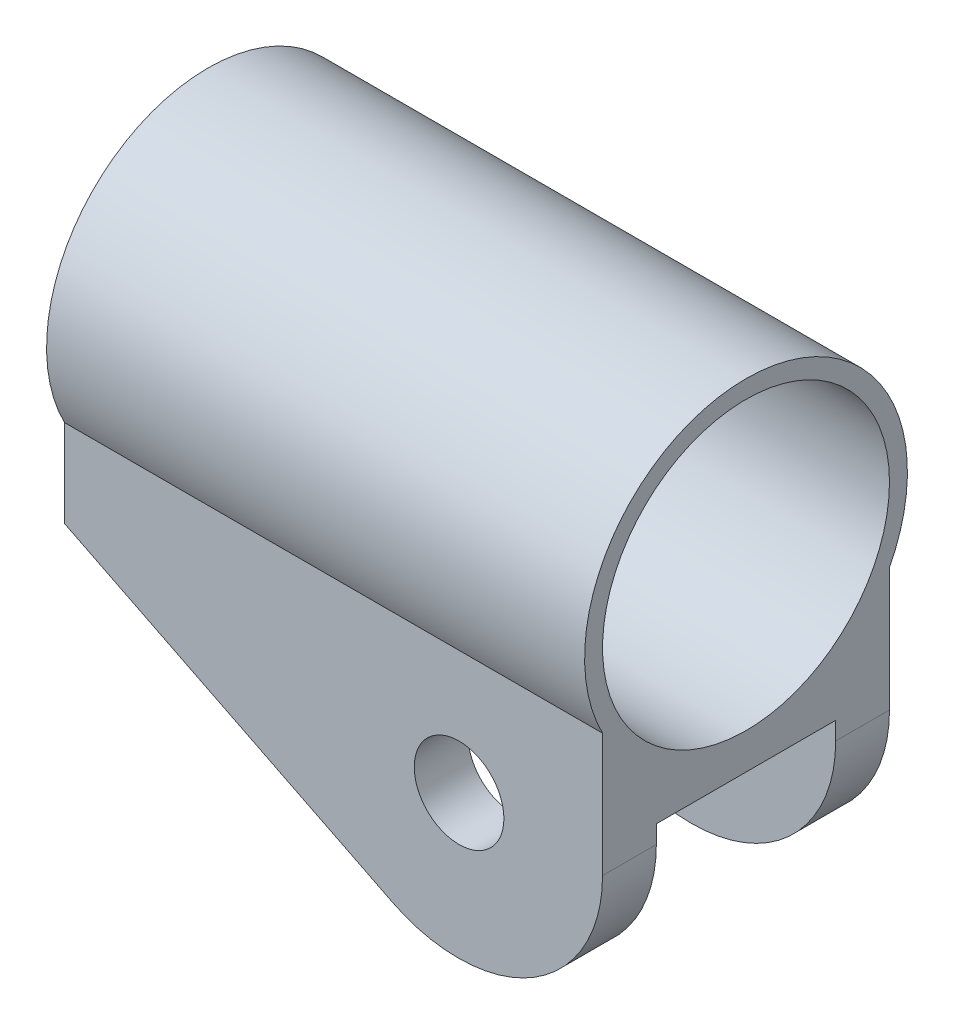
SolidWorks part; units mm, degrees
material "ABS"
ref_plane "Front Plane" through (0, 0, 0) normal (0, 0, 1) x (1, 0, 0)
ref_plane "Top Plane" through (0, 0, 0) normal (0, 1, 0) x (1, 0, 0)
ref_plane "Right Plane" through (0, 0, 0) normal (1, 0, 0) x (0, 0, -1)
sketch "Sketch1" plane through (0, 0, 0) normal (1, 0, 0) x (0, 0, -1)
  circle A0 centre (0, 0) radius 8
  circle A1 centre (0, 0) radius 9
  dimension "D1" = 16
  dimension "D2" = 1
extrude "Boss-Extrude1" add sketch "Sketch1" along normal blind 30
ref_plane "Plane1" through (0, -9, 0) normal (0, -1, 0) x (-1, 0, 0)
sketch "Sketch2" plane through (0, -9, 0) normal (0, -1, 0) x (-1, 0, 0)
  line L0 (0, -9) -> (0, 9) construction
  line L1 (-30, 9) -> (-30, -9) construction
  line L2 (0, -8) -> (-30, -8)
  line L3 (0, -8) -> (0, 8)
  line L4 (0, 8) -> (-30, 8)
  line L5 (-30, -8) -> (-30, 8)
  dimension "D1" = 8
  dimension "D2" = 8
extrude "Boss-Extrude2" add sketch "Sketch2" along normal blind 10 and the other way up to surface
sketch "Sketch3" plane through (0, 0, 8) normal (0, 0, 1) x (1, 0, 0)
  line L0 (0, -19) -> (0, -9)
  line L1 (-9.9, -9) -> (9.9, -9) construction
  line L2 (0, -19) -> (0, -4.1231) construction
  line L3 (0, -9) -> (20, -19)
  line L4 (30, -19) -> (0, -19) construction
  line L5 (20, -19) -> (0, -19)
  line L6 (30, -19) -> (30, -4.1231) construction
  dimension "D1" = 10
extrude "Cut-Extrude1" cut sketch "Sketch3" against normal through all
sketch "Sketch4" plane through (30, 0, 0) normal (1, 0, 0) x (0, 0, -1)
  line L0 (8, -19) -> (-8, -19) construction
  line L1 (-5, -19) -> (5, -19)
  line L2 (-5, -19) -> (-5, -10)
  line L3 (-5, -10) -> (5, -10)
  line L4 (5, -19) -> (5, -10)
  line L5 (-8, -19) -> (-8, -4.1231) construction
  line L6 (8, -19) -> (8, -4.1231) construction
  circle A0 centre (0, 0) radius 8 construction
  dimension "D1" = 3
  dimension "D2" = 3
  dimension "D3" = 10
extrude "Cut-Extrude2" cut sketch "Sketch4" against normal through all
fillet "Fillet1" radius 8 4 edges at (20, -19, -6.5) (20, -19, 6.5) (30, -19, -6.5) (30, -19, 6.5)
sketch "Sketch5" plane through (0, 0, 8) normal (0, 0, 1) x (1, 0, 0)
  circle A0 centre (22, -11) radius 2.5
  dimension "D1" = 5
extrude "Cut-Extrude3" cut sketch "Sketch5" against normal through all
